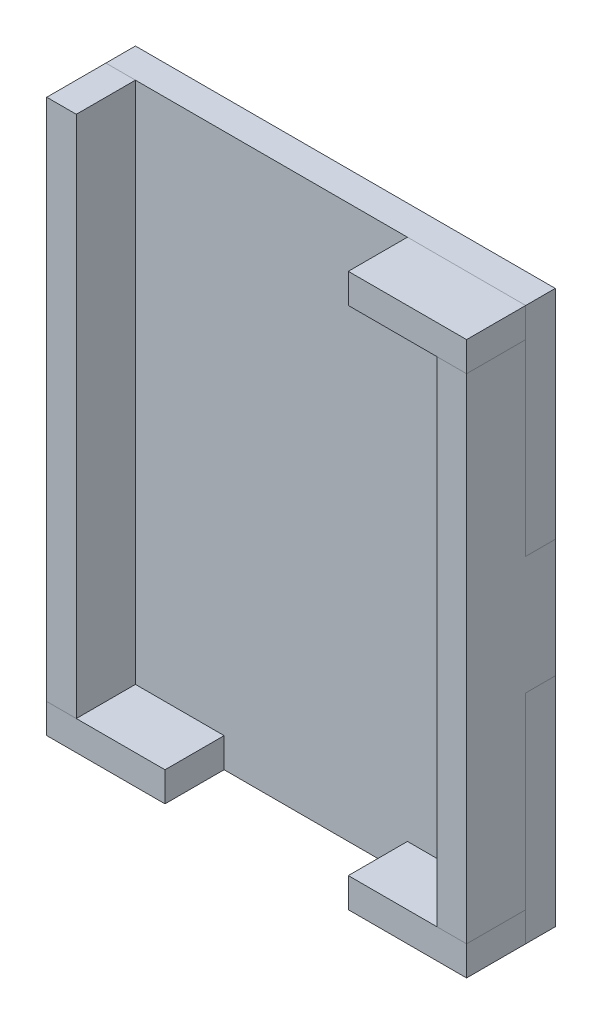
SolidWorks part; units mm, degrees
ref_plane "Plan de face" through (0, 0, 0) normal (0, 0, 1) x (1, 0, 0)
ref_plane "Plan de dessus" through (0, 0, 0) normal (0, 1, 0) x (1, 0, 0)
ref_plane "Plan de droite" through (0, 0, 0) normal (1, 0, 0) x (0, 0, -1)
sketch "Esquisse1" plane through (0, 0, 0) normal (0, 0, 1) x (1, 0, 0)
  line L0 (-45.085, 59.3725) -> (45.085, 59.3725)
  line L1 (45.085, 59.3725) -> (45.085, 12.7)
  line L2 (45.085, 12.7) -> (38.735, 12.7)
  line L3 (38.735, 12.7) -> (38.735, -12.7)
  line L4 (38.735, -12.7) -> (45.085, -12.7)
  line L5 (45.085, -12.7) -> (45.085, -59.3725)
  line L6 (45.085, -59.3725) -> (-45.085, -59.3725)
  line L7 (-45.085, -59.3725) -> (-45.085, -12.7)
  line L8 (-45.085, -12.7) -> (-38.735, -12.7)
  line L9 (-38.735, -12.7) -> (-38.735, 12.7)
  line L10 (-38.735, 12.7) -> (-45.085, 12.7)
  line L11 (-45.085, 12.7) -> (-45.085, 59.3725)
  point P10 (-38.735, 0)
  point P13 (38.735, 0)
  point P15 (-41.91, -12.7)
  point P16 (0, -59.3725)
  point P17 (0, 59.3725)
  dimension "D1" = 90.17
  dimension "D2" = 46.6725
  dimension "D3" = 25.4
  dimension "D4" = 6.35
extrude "Boss.-Extru.1" add sketch "Esquisse1" along normal mid plane 6.35
sketch "Esquisse2" plane through (0, 0, 3.175) normal (0, 0, 1) x (1, 0, 0)
  line L1 (45.085, 59.3725) -> (19.685, 59.3725)
  line L2 (45.085, 59.3725) -> (45.085, 53.0225)
  line L3 (45.085, 53.0225) -> (19.685, 53.0225)
  line L4 (19.685, 59.3725) -> (19.685, 53.0225)
  dimension "D1" = 6.35
  dimension "D2" = 25.4
extrude "Boss.-Extru.2" add sketch "Esquisse2" along normal blind 12.7 separate body
sketch "Esquisse3" plane through (0, 0, 3.175) normal (0, 0, 1) x (1, 0, 0)
  line L1 (-45.085, -59.3725) -> (-19.685, -59.3725)
  line L2 (-45.085, -59.3725) -> (-45.085, -53.0225)
  line L3 (-45.085, -53.0225) -> (-19.685, -53.0225)
  line L4 (-19.685, -59.3725) -> (-19.685, -53.0225)
  line L5 (45.085, -59.3725) -> (19.685, -59.3725)
  line L6 (45.085, -59.3725) -> (45.085, -53.0225)
  line L7 (45.085, -53.0225) -> (19.685, -53.0225)
  line L8 (19.685, -59.3725) -> (19.685, -53.0225)
  point P10 (19.685, -56.1975)
  dimension "D1" = 6.35
  dimension "D2" = 25.4
extrude "Boss.-Extru.3" add sketch "Esquisse3" along normal blind 12.7 separate body
sketch "Esquisse5" plane through (38.735, 0, 0) normal (1, 0, 0) x (0, 0, -1)
  line L0 (3.175, 12.7) -> (-3.175, 12.7)
  line L1 (-3.175, 12.7) -> (-3.175, 53.0225)
  line L2 (-3.175, 53.0225) -> (-15.875, 53.0225)
  line L3 (-15.875, 53.0225) -> (-15.875, -53.0225)
  line L4 (-15.875, -53.0225) -> (-3.175, -53.0225)
  line L5 (-3.175, -53.0225) -> (-3.175, -12.7)
  line L6 (-3.175, -12.7) -> (3.175, -12.7)
  line L7 (3.175, -12.7) -> (3.175, 12.7)
extrude "Boss.-Extru.4" add sketch "Esquisse5" along normal blind 6.35 separate body
sketch "Esquisse6" plane through (-38.735, 0, 0) normal (-1, 0, 0) x (0, 0, 1)
  line L0 (-3.175, 12.7) -> (3.175, 12.7)
  line L1 (3.175, 12.7) -> (3.175, 59.3725)
  line L2 (3.175, 59.3725) -> (15.875, 59.3725)
  line L3 (15.875, 59.3725) -> (15.875, -53.0225)
  line L4 (15.875, -53.0225) -> (3.175, -53.0225)
  line L5 (3.175, -53.0225) -> (3.175, -12.7)
  line L6 (3.175, -12.7) -> (-3.175, -12.7)
  line L7 (-3.175, -12.7) -> (-3.175, 12.7)
extrude "Boss.-Extru.5" add sketch "Esquisse6" along normal blind 6.35 separate body
